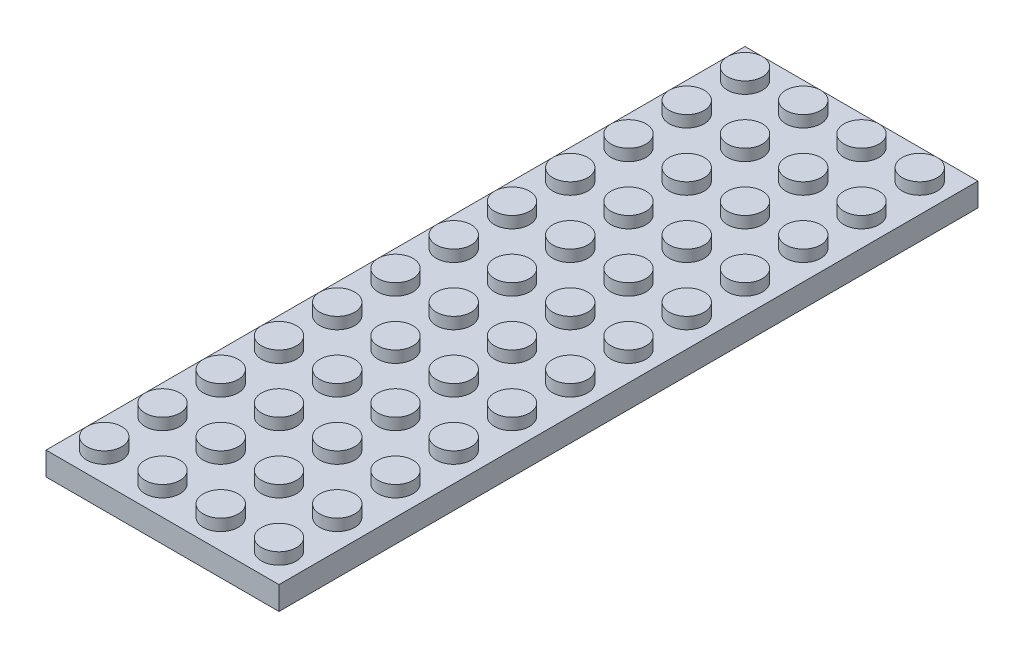
SolidWorks part; units mm, degrees
ref_plane "Front Plane" through (0, 0, 0) normal (0, 0, 1) x (1, 0, 0)
ref_plane "Top Plane" through (0, 0, 0) normal (0, 1, 0) x (1, 0, 0)
ref_plane "Right Plane" through (0, 0, 0) normal (1, 0, 0) x (0, 0, -1)
sketch "Sketch1" plane through (0, 0, 0) normal (0, 1, 0) x (1, 0, 0)
  line L1 (0, 0) -> (32, 0)
  line L2 (0, 0) -> (0, 96)
  line L3 (0, 96) -> (32, 96)
  line L4 (32, 0) -> (32, 96)
  dimension "D1" = 32
  dimension "D2" = 96
extrude "Boss-Extrude1" add sketch "Sketch1" along normal blind 3.2
sketch "Sketch2" plane through (0, 3.2, 0) normal (0, 1, 0) x (1, 0, 0)
  line L0 (16, 0) -> (16, 96) construction
  line L1 (0, 0) -> (32, 0) construction
  line L2 (32, 96) -> (0, 96) construction
  line L3 (32, 0) -> (32, 4) construction
  line L4 (32, 0) -> (32, 96) construction
  line L5 (32, 4) -> (28, 4) construction
  circle A0 centre (28, 4) radius 2.4
  dimension "D3" = 4.8
  dimension "D1" = 4
  dimension "D2" = 4
extrude "Boss-Extrude2" add sketch "Sketch2" along normal blind 1.6
pattern_linear "LPattern1" count 4 spacing 8 along (-1, 0, 0) count 12 spacing 8 along (0, 0, -1) of "Boss-Extrude2"
shell "Shell1" thickness 1.6
